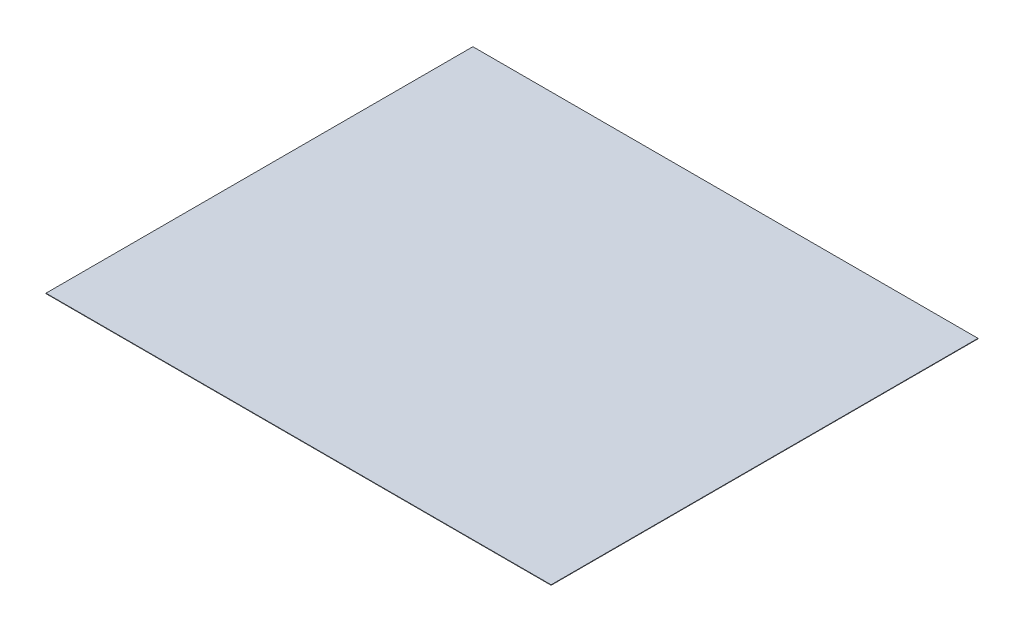
SolidWorks part; units mm, degrees
ref_plane "Front Plane" through (0, 0, 0) normal (0, 0, 1) x (1, 0, 0)
ref_plane "Top Plane" through (0, 0, 0) normal (0, 1, 0) x (1, 0, 0)
ref_plane "Right Plane" through (0, 0, 0) normal (1, 0, 0) x (0, 0, -1)
sketch "Sketch2" plane through (0, 0, 0) normal (0, 1, 0) x (1, 0, 0)
  line L1 (-1009.5256, 963.1) -> (1250.4744, 963.1)
  line L2 (-1009.5256, 963.1) -> (-1009.5256, -946.9)
  line L3 (-1009.5256, -946.9) -> (1250.4744, -946.9)
  line L4 (1250.4744, 963.1) -> (1250.4744, -946.9)
  dimension "D1" = 2260
  dimension "D2" = 1910
extrude "Boss-Extrude1" add sketch "Sketch2" along normal blind 2
